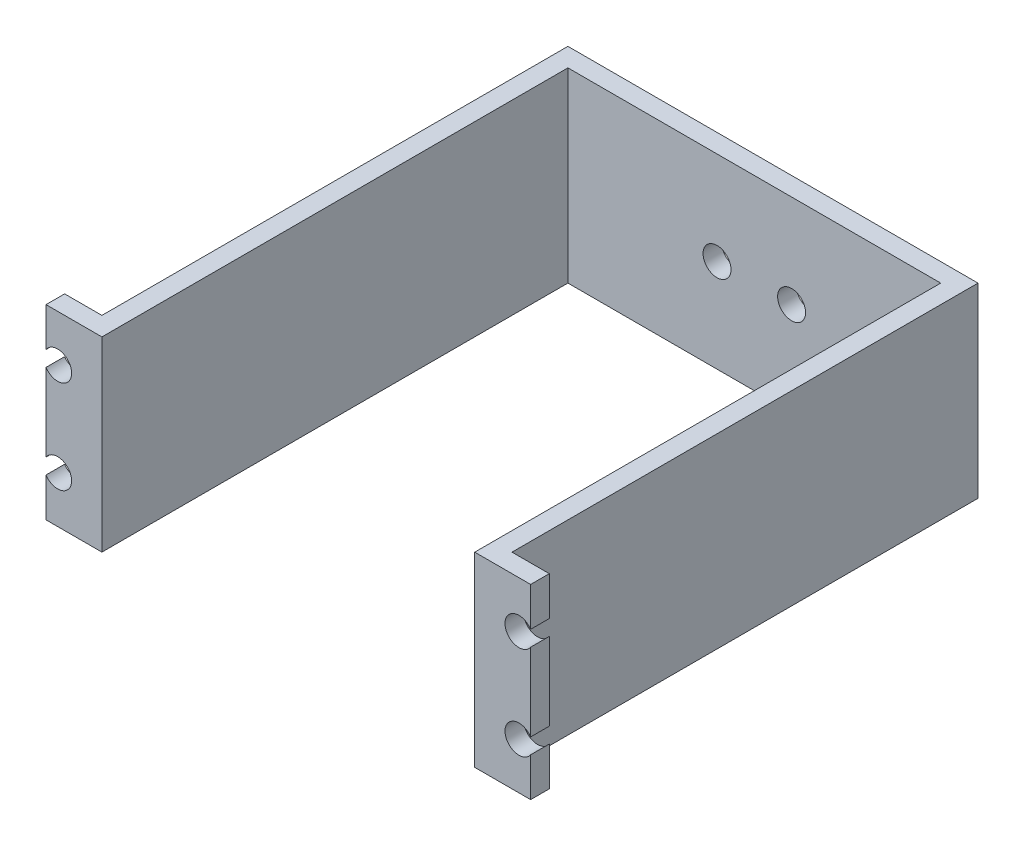
SolidWorks part; units mm, degrees
ref_plane "Plan de face" through (0, 0, 0) normal (0, 0, 1) x (1, 0, 0)
ref_plane "Plan de dessus" through (0, 0, 0) normal (0, 1, 0) x (1, 0, 0)
ref_plane "Plan de droite" through (0, 0, 0) normal (1, 0, 0) x (0, 0, -1)
sketch "Esquisse1" plane through (0, 0, 0) normal (0, 0, 1) x (1, 0, 0)
  line L1 (0, 0) -> (44, 0)
  line L2 (0, 0) -> (0, 20)
  line L3 (0, 20) -> (44, 20)
  line L4 (44, 0) -> (44, 20)
  dimension "D1" = 20
  dimension "D2" = 44
extrude "Boss.-Extru.1" add sketch "Esquisse1" along normal blind 2
sketch "Esquisse2" plane through (0, 0, 2) normal (0, 0, 1) x (1, 0, 0)
  line L0 (0, 0) -> (44, 0) construction
  line L1 (0, 20) -> (2, 20)
  line L2 (0, 20) -> (0, 0)
  line L3 (0, 0) -> (2, 0)
  line L4 (2, 20) -> (2, 0)
  line L6 (44, 20) -> (42, 20)
  line L7 (44, 20) -> (44, 0)
  line L8 (44, 0) -> (42, 0)
  line L9 (42, 20) -> (42, 0)
  dimension "D1" = 2
  dimension "D2" = 2
extrude "Boss.-Extru.2" add sketch "Esquisse2" along normal blind 50
sketch "Esquisse3" plane through (0, 0, 0) normal (-1, 0, 0) x (0, 0, 1)
  line L0 (52, 0) -> (0, 0) construction
  line L1 (52, 20) -> (50, 20)
  line L2 (52, 20) -> (52, 0)
  line L3 (52, 0) -> (50, 0)
  line L4 (50, 20) -> (50, 0)
  dimension "D1" = 2
extrude "Boss.-Extru.3" add sketch "Esquisse3" along normal blind 4
sketch "Esquisse4" plane through (44, 0, 0) normal (1, 0, 0) x (0, 0, -1)
  line L0 (-52, 0) -> (0, 0) construction
  line L1 (-52, 20) -> (-50, 20)
  line L2 (-52, 20) -> (-52, 0)
  line L3 (-52, 0) -> (-50, 0)
  line L4 (-50, 20) -> (-50, 0)
  dimension "D1" = 2
extrude "Boss.-Extru.4" add sketch "Esquisse4" along normal blind 4
sketch "Esquisse5" plane through (0, 0, 2) normal (0, 0, 1) x (1, 0, 0)
  line L0 (42, 20) -> (2, 20) construction
  line L1 (2, 0) -> (2, 20) construction
  line L2 (42, 20) -> (42, 0) construction
  circle A0 centre (18, 10) radius 1.5
  circle A1 centre (26, 10) radius 1.5
  dimension "D5" = 3
  dimension "D6" = 3
  dimension "D1" = 10
  dimension "D2" = 16
  dimension "D3" = 10
  dimension "D4" = 16
extrude "Enlèv. mat.-Extru.1" cut sketch "Esquisse5" against normal blind 4
sketch "Esquisse6" plane through (0, 0, 52) normal (0, 0, 1) x (1, 0, 0)
  line L0 (2, 0) -> (2, 20) construction
  line L1 (42, 20) -> (42, 0) construction
  line L2 (48, 20) -> (42, 20) construction
  line L3 (42, 0) -> (48, 0) construction
  line L4 (2, 20) -> (-4, 20) construction
  line L5 (-4, 0) -> (2, 0) construction
  circle A0 centre (46.75, 15) radius 1.5
  circle A1 centre (46.75, 5) radius 1.5
  circle A2 centre (-2.75, 15) radius 1.5
  circle A3 centre (-2.75, 5) radius 1.5
  dimension "D1" = 3
  dimension "D2" = 3
  dimension "D3" = 3
  dimension "D4" = 3
  dimension "D5" = 4.75
  dimension "D6" = 4.75
  dimension "D7" = 4.75
  dimension "D8" = 4.75
  dimension "D9" = 5
  dimension "D10" = 5
  dimension "D11" = 5
  dimension "D12" = 5
extrude "Enlèv. mat.-Extru.2" cut sketch "Esquisse6" against normal blind 4
